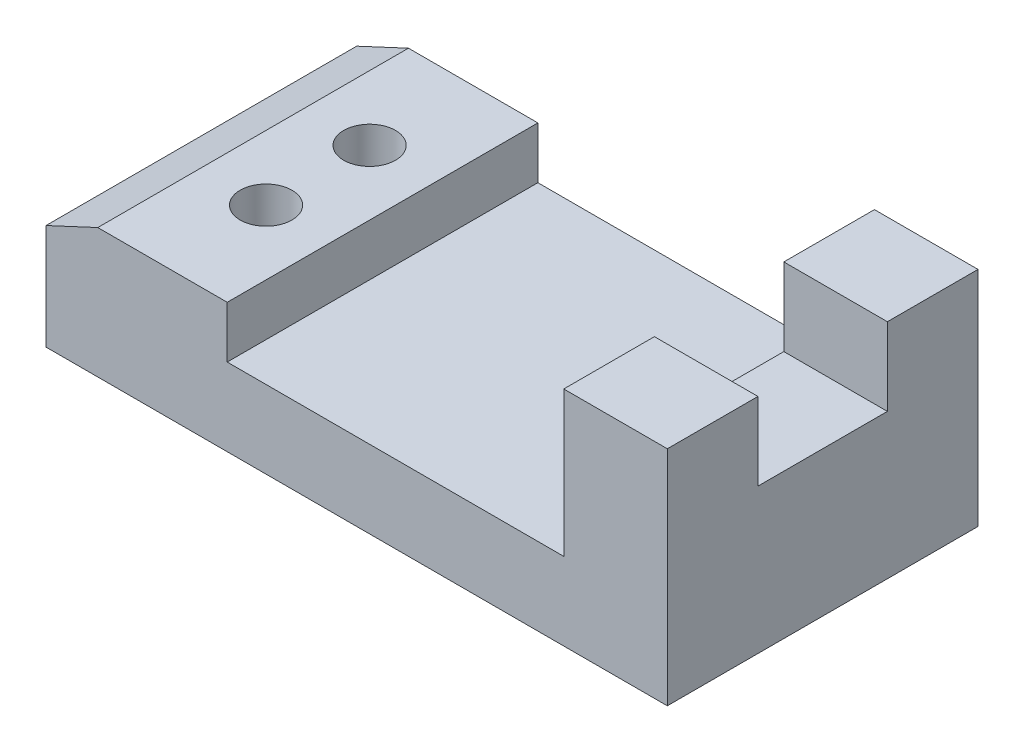
SolidWorks part; units mm, degrees
ref_plane "Front Plane" through (0, 0, 0) normal (0, 0, 1) x (1, 0, 0)
ref_plane "Top Plane" through (0, 0, 0) normal (0, 1, 0) x (1, 0, 0)
ref_plane "Right Plane" through (0, 0, 0) normal (1, 0, 0) x (0, 0, -1)
sketch "Sketch1" plane through (0, 0, 0) normal (0, 0, 1) x (1, 0, 0)
  line L0 (0, 0) -> (120, 0)
  line L1 (120, 0) -> (120, 43)
  line L2 (120, 43) -> (100, 43)
  line L3 (100, 43) -> (100, 15)
  line L4 (100, 15) -> (35, 15)
  line L5 (35, 15) -> (35, 25)
  line L6 (35, 25) -> (10, 25)
  line L7 (0, 0) -> (0, 20.3369)
  line L8 (0, 20.3369) -> (10, 25)
  dimension "D1" = 120
  dimension "D2" = 43
  dimension "D3" = 20
  dimension "D4" = 10
  dimension "D5" = 35
  dimension "D6" = 15
  dimension "D7" = 25
  dimension "D8" = 25
extrude "Boss-Extrude1" add sketch "Sketch1" along normal blind 60
sketch "Sketch2" plane through (0, 43, 0) normal (0, 1, 0) x (1, 0, 0)
  line L0 (127.5423, -30) -> (-12.8395, -30) construction
  line L1 (100, -42.5) -> (100, -17.5)
  line L2 (100, -60) -> (100, 0) construction
  line L3 (100, -17.5) -> (120, -17.5)
  line L4 (120, -60) -> (120, 0) construction
  line L5 (120, -17.5) -> (120, -42.5)
  line L6 (120, -42.5) -> (100, -42.5)
  line L8 (100, -60) -> (35, -60) construction
  dimension "D1" = 12.5
  dimension "D2" = 25
  dimension "D3" = 30
extrude "Cut-Extrude1" cut sketch "Sketch2" against normal blind 15
sketch "Sketch3" plane through (0, 25, 0) normal (0, 1, 0) x (1, 0, 0)
  line L0 (35, 0) -> (10, 0) construction
  line L1 (22.5, -76.2543) -> (22.5, 20.5897) construction
  line L2 (35, -60) -> (10, -60) construction
  circle A0 centre (22.5, -40) radius 5
  circle A1 centre (22.5, -20) radius 5
  point P11 (22.5, -60)
  dimension "D1" = 10
  dimension "D2" = 10
  dimension "D3" = 20
  dimension "D4" = 20
extrude "Cut-Extrude2" cut sketch "Sketch3" against normal through all both and the other way through all
ref_plane "Plane1" through (0, 0, 62) normal (0, 0, 1) x (1, 0, 0)
sketch "Sketch6" plane through (0, 0, 62) normal (0, 0, 1) x (1, 0, 0)
  line L0 (0, 20.3369) -> (0, 0) construction
  line L1 (120, 43) -> (100, 43) construction
  point P0 (-2, 45)
  dimension "D1" = 2
  dimension "D2" = 2
